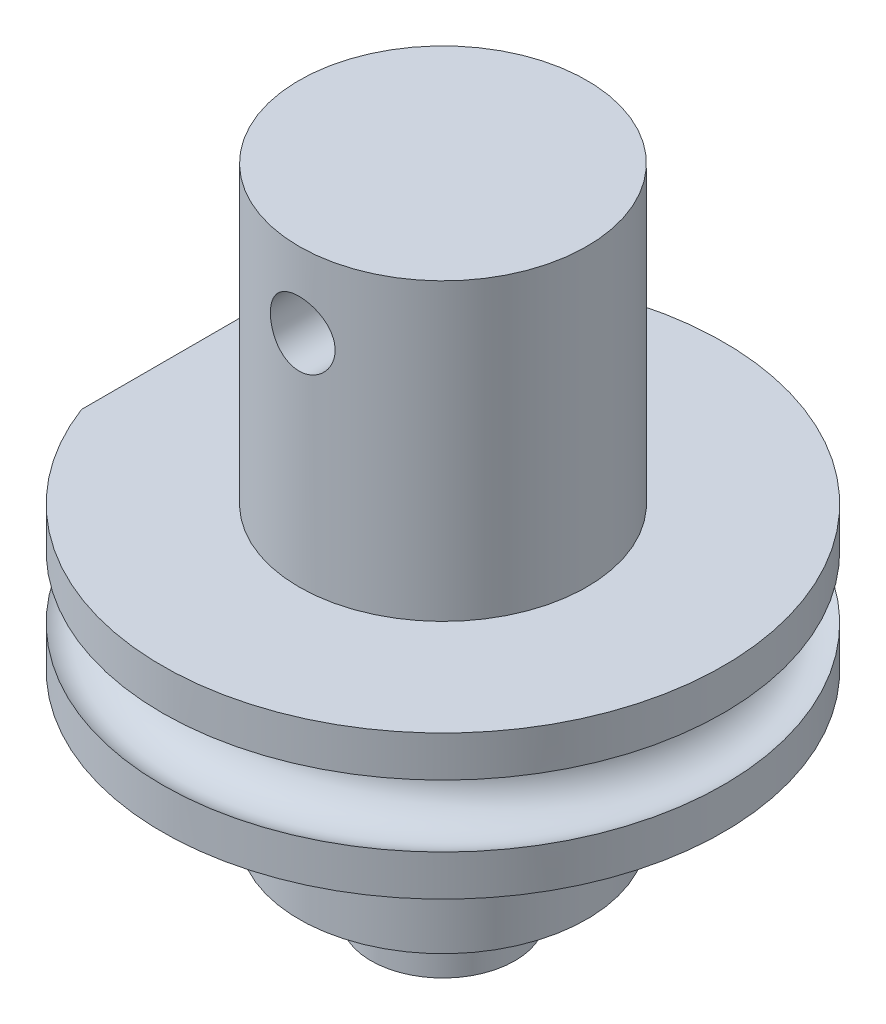
SolidWorks part; units mm, degrees
ref_plane "前视基准面" through (0, 0, 0) normal (0, 0, 1) x (1, 0, 0)
ref_plane "上视基准面" through (0, 0, 0) normal (0, 1, 0) x (1, 0, 0)
ref_plane "右视基准面" through (0, 0, 0) normal (1, 0, 0) x (0, 0, -1)
other "Configuration Table"
sketch "草图1" plane through (0, 0, 0) normal (0, 1, 0) x (1, 0, 0)
  circle A0 centre (0, 0) radius 7.8
  dimension "D1" = 15.6
extrude "凸台-拉伸1" add sketch "草图1" along normal blind 4
sketch "草图2" plane through (0, 4, 0) normal (0, 1, 0) x (1, 0, 0)
  circle A0 centre (0, 0) radius 4
  dimension "D1" = 8
extrude "凸台-拉伸2" add sketch "草图2" along normal blind 8.2
ref_plane "基准面2" through (0, 2, 0) normal (0, 1, 0) x (1, 0, 0)
sketch "草图5" plane through (0, 2, 0) normal (0, 1, 0) x (1, 0, 0)
  circle A0 centre (0, 0) radius 7.3
  circle A1 centre (0, 0) radius 7.8 construction
  dimension "D1" = 0.5
sweep "切除-扫描1" cut path "草图5" circular profile diameter 2 parameters "D3"=2
ref_plane "基准面3" through (0, 0, -4) normal (0, 0, -1) x (-1, 0, 0)
sketch "草图10" plane through (0, 0, -4) normal (0, 0, -1) x (-1, 0, 0)
  line L0 (4, 12.2) -> (-4, 12.2) construction
  line L1 (0, 10.1) -> (0, 12.2) construction
  circle A0 centre (0, 10.1) radius 0.9
  dimension "D1" = 1.8
  dimension "D2" = 2.1
extrude "切除-拉伸3" cut sketch "草图10" against normal through all
sketch "草图12" plane through (0, 0, 0) normal (0, -1, 0) x (1, 0, 0)
  circle A0 centre (0, 0) radius 4
  dimension "D1" = 8
extrude "凸台-拉伸3" add sketch "草图12" along normal blind 4
sketch "草图13" plane through (0, -4, 0) normal (0, -1, 0) x (1, 0, 0)
  line L0 (-1, 1.7321) -> (-1, -1.7321)
  circle A0 centre (0, 0) radius 2
  dimension "D1" = 4
  dimension "D2" = 1
extrude "凸台-拉伸4" add sketch "草图13" along normal blind 2 contours L0 A0
ref_plane "基准面4" through (-7.8, 0, 0) normal (-1, 0, 0) x (0, 0, 1)
sketch "草图14" plane through (-7.8, 0, 0) normal (-1, 0, 0) x (0, 0, 1)
  line L0 (8.58, 2) -> (-8.58, 2) construction
  circle A0 centre (0, 2) radius 0.9
  dimension "D1" = 1.8
extrude "切除-拉伸4" cut sketch "草图14" against normal blind 5
sketch "草图15" plane through (-7.8, 0, 0) normal (-1, 0, 0) x (0, 0, 1)
  line L0 (7.8, 4) -> (-7.8, 4) construction
  line L1 (-3.7198, 4) -> (4.0505, 4)
  line L2 (-3.7198, 4) -> (-3.7198, 0)
  line L3 (-3.7198, 0) -> (4.0505, 0)
  line L4 (4.0505, 4) -> (4.0505, 0)
extrude "切除-拉伸5" cut sketch "草图15" against normal blind 0.5
